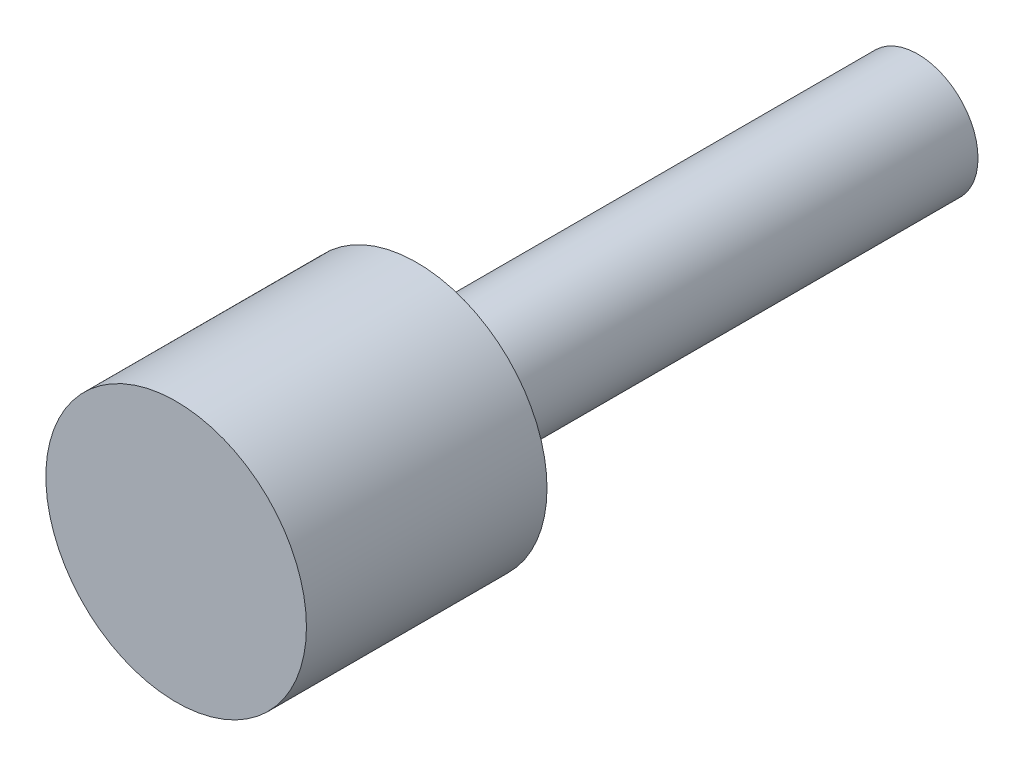
SolidWorks part; units mm, degrees
ref_plane "前视基准面" through (0, 0, 0) normal (0, 0, 1) x (1, 0, 0)
ref_plane "上视基准面" through (0, 0, 0) normal (0, 1, 0) x (1, 0, 0)
ref_plane "右视基准面" through (0, 0, 0) normal (1, 0, 0) x (0, 0, -1)
sketch "草图1" plane through (0, 0, 0) normal (0, 0, 1) x (1, 0, 0)
  circle A0 centre (0, 0) radius 3
  dimension "D1" = 6
extrude "凸台-拉伸1" add sketch "草图1" along normal mid plane 25
sketch "草图2" plane through (0, 0, 12.5) normal (0, 0, 1) x (1, 0, 0)
  circle A0 centre (0, 0) radius 6.5
  dimension "D1" = 13
extrude "凸台-拉伸2" add sketch "草图2" along normal blind 12
